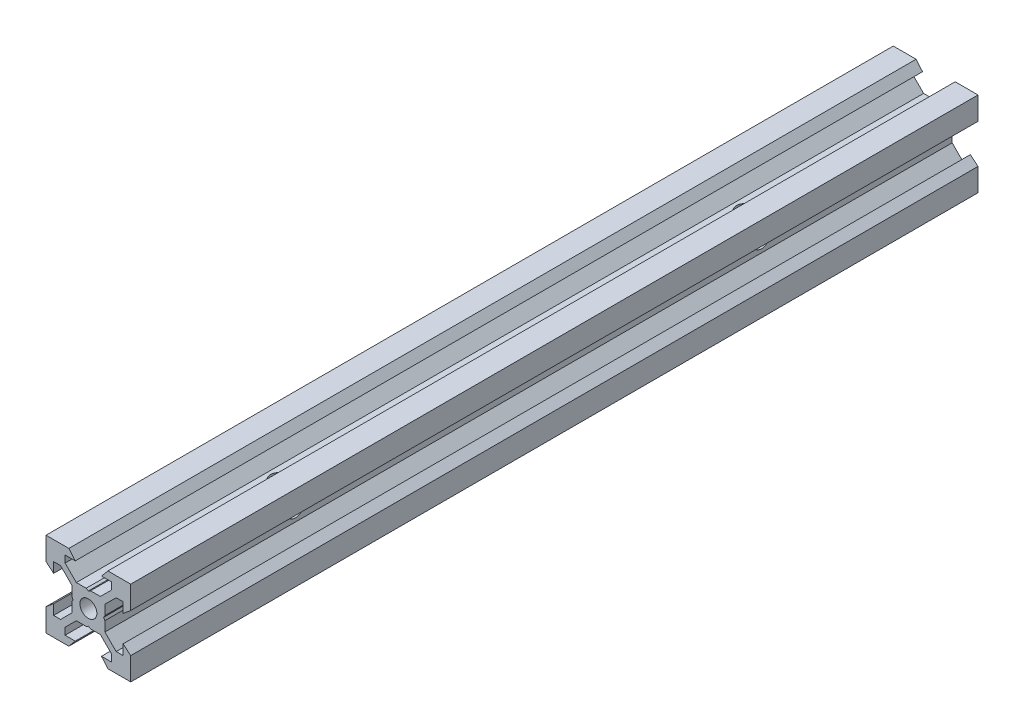
SolidWorks part; units mm, degrees
material "3.3535 (EN-AW 5754)"
ref_plane "Front Plane" through (0, 0, 0) normal (0, 0, 1) x (1, 0, 0)
ref_plane "Top Plane" through (0, 0, 0) normal (0, 1, 0) x (1, 0, 0)
ref_plane "Right Plane" through (0, 0, 0) normal (1, 0, 0) x (0, 0, -1)
sketch "Sketch1" plane through (0, 0, 0) normal (0, 0, 1) x (1, 0, 0)
  line L0 (10, 10) -> (4.6104, 10) construction
  line L1 (10, 10) -> (10, 4.6104) construction
  line L2 (10, -10) -> (10, -4.6104) construction
  line L3 (10, -10) -> (4.6104, -10) construction
  line L4 (10, 10) -> (10, 4.6104)
  line L5 (6.5607, 5.5) -> (8.2, 5.5)
  line L6 (5.5, 8.2) -> (5.5, 6.5607)
  line L7 (10, 10) -> (4.6104, 10)
  line L8 (10, 10) -> (10, 4.6104)
  line L9 (6.5607, 5.5) -> (3.9, 2.8393)
  line L10 (5.5, 6.5607) -> (2.8393, 3.9)
  line L11 (10, 4.6104) -> (8.2, 3.1)
  line L12 (4.6104, 10) -> (3.1, 8.2)
  line L13 (8.2, 3.1) -> (8.2, 5.5)
  line L14 (3.1, 8.2) -> (5.5, 8.2)
  line L15 (-6.5607, 5.5) -> (-8.2, 5.5)
  line L16 (6.5607, -5.5) -> (8.2, -5.5)
  line L17 (3.1, -8.2) -> (5.5, -8.2)
  line L18 (8.2, -3.1) -> (8.2, -5.5)
  line L19 (4.6104, -10) -> (3.1, -8.2)
  line L20 (10, -4.6104) -> (8.2, -3.1)
  line L21 (0.5196, -3.9) -> (0, -3.6)
  line L22 (0.5196, 3.9) -> (0, 3.6)
  line L23 (3.6, 0) -> (3.9, -0.5196)
  line L24 (3.9, 0.5196) -> (3.6, 0)
  line L25 (3.9, 0.5196) -> (3.9, 2.8393)
  line L26 (2.8393, 3.9) -> (0.5196, 3.9)
  line L27 (3.9, -2.8393) -> (3.9, -0.5196)
  line L28 (2.8393, -3.9) -> (0.5196, -3.9)
  line L29 (5.5, -6.5607) -> (2.8393, -3.9)
  line L30 (6.5607, -5.5) -> (3.9, -2.8393)
  line L31 (10, -10) -> (10, -4.6104)
  line L32 (10, -10) -> (4.6104, -10)
  line L33 (5.5, -8.2) -> (5.5, -6.5607)
  line L34 (-6.5607, -5.5) -> (-8.2, -5.5)
  line L35 (10, -10) -> (10, -4.6104)
  line L36 (0, 0) -> (0, 8.2) construction
  line L37 (-10, -10) -> (-4.6104, -10) construction
  line L38 (-10, -10) -> (-10, -4.6104) construction
  line L39 (-10, 10) -> (-10, 4.6104) construction
  line L40 (-10, 10) -> (-4.6104, 10) construction
  line L41 (-10, -10) -> (-10, -4.6104)
  line L43 (-5.5, -8.2) -> (-5.5, -6.5607)
  line L44 (-10, -10) -> (-4.6104, -10)
  line L45 (-10, -10) -> (-10, -4.6104)
  line L46 (-6.5607, -5.5) -> (-3.9, -2.8393)
  line L47 (-5.5, -6.5607) -> (-2.8393, -3.9)
  line L48 (-2.8393, -3.9) -> (-0.5196, -3.9)
  line L49 (-3.9, -2.8393) -> (-3.9, -0.5196)
  line L50 (-2.8393, 3.9) -> (-0.5196, 3.9)
  line L51 (-3.9, 0.5196) -> (-3.9, 2.8393)
  line L52 (-3.9, 0.5196) -> (-3.6, 0)
  line L53 (-3.6, 0) -> (-3.9, -0.5196)
  line L54 (-0.5196, 3.9) -> (0, 3.6)
  line L55 (-0.5196, -3.9) -> (0, -3.6)
  line L56 (-10, -4.6104) -> (-8.2, -3.1)
  line L57 (-4.6104, -10) -> (-3.1, -8.2)
  line L58 (-8.2, -3.1) -> (-8.2, -5.5)
  line L59 (-3.1, -8.2) -> (-5.5, -8.2)
  line L60 (-10, -10) -> (10, -10) construction
  line L61 (-10, -10) -> (-10, 10) construction
  line L62 (-3.1, 8.2) -> (-5.5, 8.2)
  line L63 (-8.2, 3.1) -> (-8.2, 5.5)
  line L64 (-4.6104, 10) -> (-3.1, 8.2)
  line L65 (-10, 4.6104) -> (-8.2, 3.1)
  line L66 (-5.5, 6.5607) -> (-2.8393, 3.9)
  line L67 (-6.5607, 5.5) -> (-3.9, 2.8393)
  line L68 (-10, 10) -> (-10, 4.6104)
  line L69 (-10, 10) -> (-4.6104, 10)
  line L70 (-5.5, 8.2) -> (-5.5, 6.5607)
  line L71 (-10, 10) -> (10, 10) construction
  line L72 (-10, 10) -> (-10, 4.6104)
  line L73 (10, -10) -> (10, 10) construction
  line L74 (-10, -10) -> (10, 10) construction
  line L75 (-10, 10) -> (10, -10) construction
  circle A0 centre (0, 0) radius 2
  dimension "D7" = 4
  dimension "D1" = 20
  dimension "D2" = 5.3896
  dimension "D3" = 4.5
  dimension "D4" = 50
  dimension "D5" = 1.8
  dimension "D6" = 1.5104
  dimension "D8" = 5.5
  dimension "D9" = 120
  dimension "D10" = 0.3
  dimension "D11" = 2.3197
  dimension "D12" = 7.8
  dimension "D13" = 7.8
  dimension "D14" = 1.5
  dimension "D15" = 2.6607
extrude "Boss-Extrude1" add sketch "Sketch1" along normal blind 200 contours L70 L62 L64 L69 L68 L65 L63 L15 L67 L51 L52 L53 L49 L46 L34 L58 L56 L41 L44 L57 L59 L43 L47 L48 L55 L21 L28 L29 L33 L17 L19 L32 L31 L20 L18 L16 L30 L27 L23 L24 L25 L9 L5 L13 L11 L4 L7 L12 L14 L6 L10
sketch "Sketch2" plane through (0, -3.9, 0) normal (0, -1, 0) x (-1, 0, 0)
  line L0 (0, -200) -> (0, -155) construction
  line L1 (0, -200) -> (0, 0) construction
  line L2 (0, 0) -> (0, -45) construction
  circle A0 centre (0, -155) radius 2
  circle A1 centre (0, -45) radius 2
  dimension "D2" = 4
  dimension "D4" = 4
  dimension "D1" = 45
  dimension "D3" = 45
extrude "Cut-Extrude1" cut sketch "Sketch2" against normal through all both and the other way through all
sketch "Sketch3" plane through (3.9, 0, 0) normal (1, 0, 0) x (0, 0, -1)
  line L0 (0, 0) -> (-45, 0) construction
  line L1 (-200, 0) -> (0, 0) construction
  line L2 (-200, 0) -> (-155, 0) construction
  circle A0 centre (-45, 0) radius 2
  circle A1 centre (-155, 0) radius 2
  dimension "D2" = 4
  dimension "D4" = 4
  dimension "D1" = 45
  dimension "D3" = 45
extrude "Cut-Extrude2" cut sketch "Sketch3" against normal through all both
